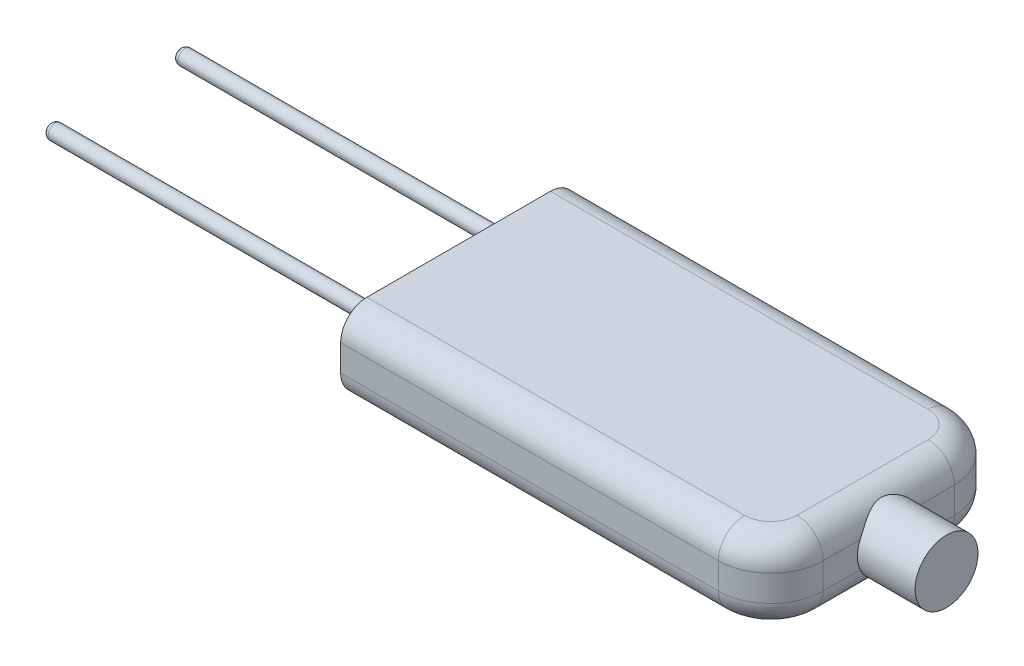
SolidWorks part; units mm, degrees
ref_plane "Front Plane" through (0, 0, 0) normal (0, 0, 1) x (1, 0, 0)
ref_plane "Top Plane" through (0, 0, 0) normal (0, 1, 0) x (1, 0, 0)
ref_plane "Right Plane" through (0, 0, 0) normal (1, 0, 0) x (0, 0, -1)
sketch "Sketch1" plane through (0, 0, 0) normal (0, 1, 0) x (1, 0, 0)
  line L1 (0, 0) -> (72, 0)
  line L2 (0, 0) -> (0, 45)
  line L3 (0, 45) -> (72, 45)
  line L4 (82, 10) -> (82, 35)
  arc A0 (72, 45) -> (82, 35) centre (72, 35) cw
  arc A1 (72, 0) -> (82, 10) centre (72, 10) ccw
  point P7 (82, 45)
  point P10 (82, 0)
  dimension "D3" = 10
  dimension "D1" = 45
  dimension "D2" = 82
extrude "Boss-Extrude1" add sketch "Sketch1" along normal blind 15
fillet "Fillet1" radius 5 10 edges at (36, 0, -45) (79.0711, 0, -42.0711) (82, 0, -22.5) (79.0711, 0, -2.9289) (36, 15, -45) (79.0711, 15, -42.0711) (82, 15, -22.5) (79.0711, 15, -2.9289) (36, 0, 0) (36, 15, 0)
sketch "Sketch2" plane through (82, 0, 0) normal (1, 0, 0) x (0, 0, -1)
  line L0 (22.5, 10) -> (22.5, 5) construction
  line L1 (35, 10) -> (10, 10) construction
  line L2 (10, 5) -> (35, 5) construction
  circle A0 centre (22.5, 7.5) radius 6
  dimension "D1" = 12
extrude "Boss-Extrude2" add sketch "Sketch2" along normal mid plane 22
sketch "Sketch3" plane through (0, 0, 0) normal (-1, 0, 0) x (0, 0, 1)
  line L0 (-45, 7.5) -> (0, 7.5) construction
  line L1 (-45, 10) -> (-45, 5) construction
  line L2 (0, 10) -> (0, 5) construction
  line L3 (-22.5, 15) -> (-22.5, 0) construction
  line L4 (-40, 15) -> (-5, 15) construction
  line L5 (-40, 0) -> (-5, 0) construction
  circle A0 centre (-34.85, 7.5) radius 1.4
  circle A1 centre (-10.15, 7.5) radius 1.4
  dimension "D1" = 2.8
  dimension "D2" = 24.7
extrude "Boss-Extrude3" add sketch "Sketch3" along normal blind 65.5
fillet "Fillet2" radius 1 2 edges at (-65.5, 7.5, -33.45) (-65.5, 7.5, -11.55)
